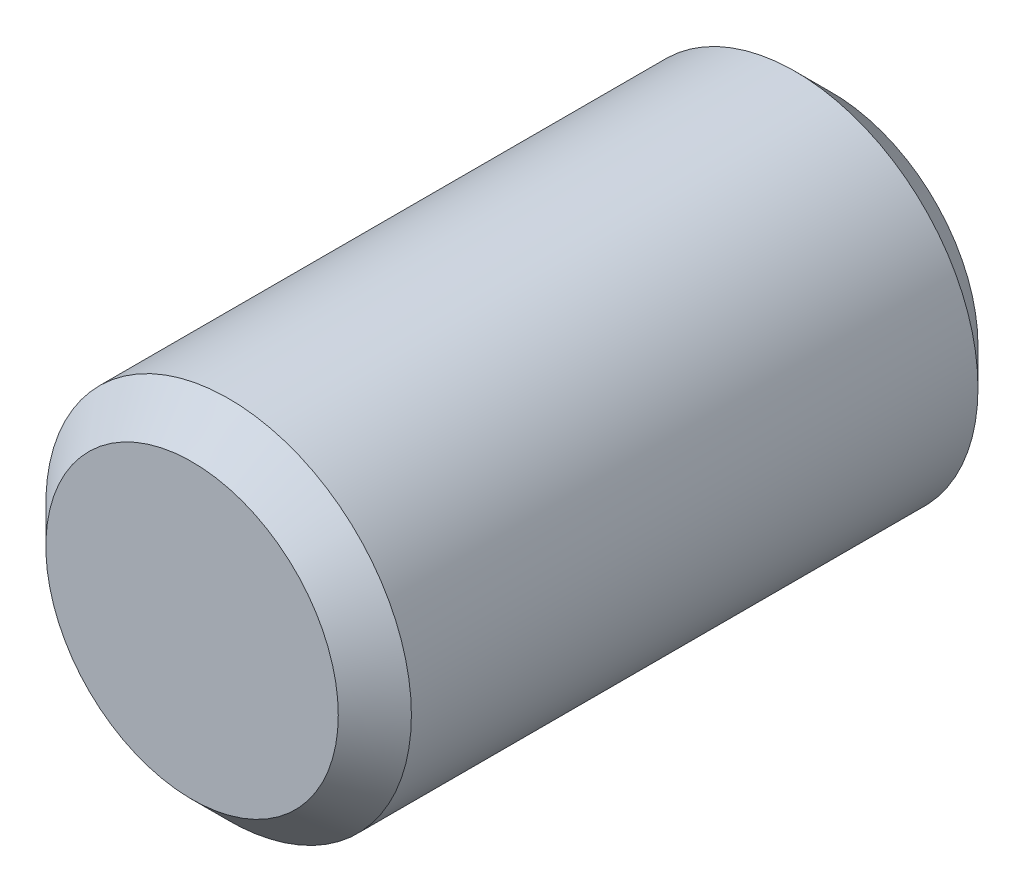
SolidWorks part; units mm, degrees
ref_plane "Ön Düzlem" through (0, 0, 0) normal (0, 0, 1) x (1, 0, 0)
ref_plane "Üst Düzlem" through (0, 0, 0) normal (0, 1, 0) x (1, 0, 0)
ref_plane "Sağ Düzlem" through (0, 0, 0) normal (1, 0, 0) x (0, 0, -1)
sketch "Sketch1" plane through (0, 0, 0) normal (0, 0, 1) x (1, 0, 0)
  circle A0 centre (0, 0) radius 5
  dimension "D1" = 10
extrude "Boss-Extrude1" add sketch "Sketch1" along normal mid plane 17.5
chamfer "Chamfer1" distance 1 angle 45 2 edges at (5, 0, -8.75) (5, 0, 8.75)
